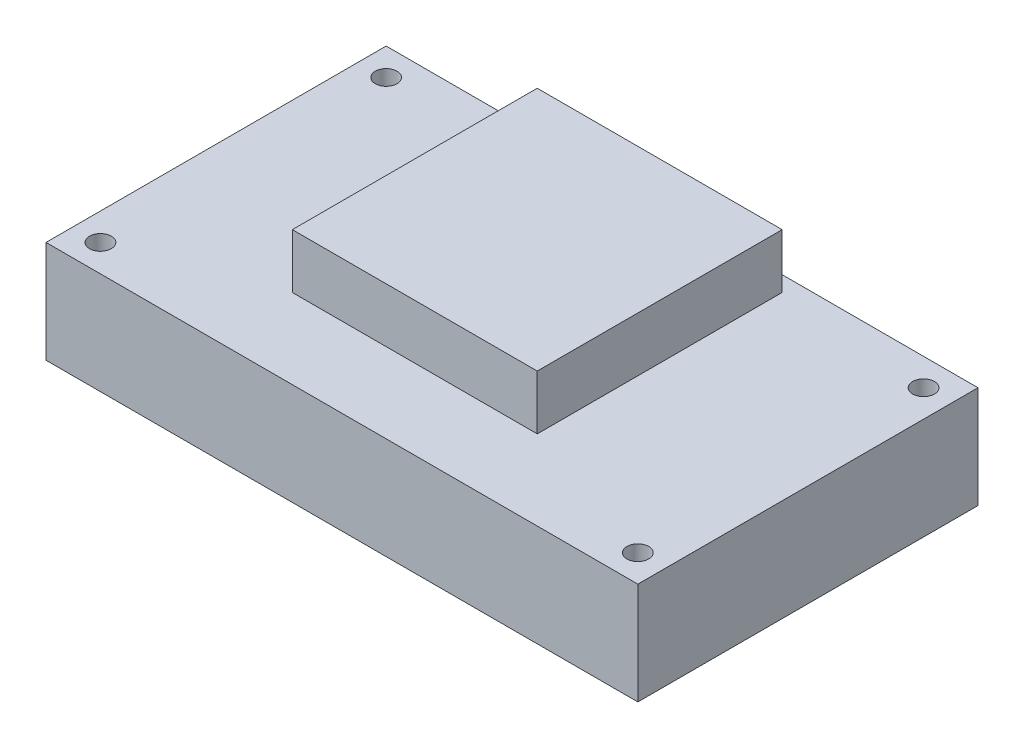
SolidWorks part; units mm, degrees
ref_plane "前视基准面" through (0, 0, 0) normal (0, 0, 1) x (1, 0, 0)
ref_plane "上视基准面" through (0, 0, 0) normal (0, 1, 0) x (1, 0, 0)
ref_plane "右视基准面" through (0, 0, 0) normal (1, 0, 0) x (0, 0, -1)
sketch "草图1" plane through (0, 0, 0) normal (0, 1, 0) x (1, 0, 0)
  line L0 (0, -55) -> (0, 55) construction
  line L1 (-43.5, 25) -> (43.5, 25)
  line L2 (-43.5, 25) -> (-43.5, -25)
  line L3 (-43.5, -25) -> (43.5, -25)
  line L4 (43.5, 25) -> (43.5, -25)
  line L5 (-43.5, 25) -> (43.5, -25) construction
  line L6 (-43.5, -25) -> (43.5, 25) construction
  line L7 (-55, 0) -> (55, 0) construction
  circle A0 centre (-39.5, 21) radius 1.6
  circle A1 centre (39.5, 21) radius 1.6
  circle A2 centre (39.5, -21) radius 1.6
  circle A3 centre (-39.5, -21) radius 1.6
  point P0 (0, 0)
  dimension "D3" = 3.2
  dimension "D4" = 4
  dimension "D5" = 4
  dimension "D1" = 87
  dimension "D2" = 50
extrude "凸台-拉伸1" add sketch "草图1" along normal blind 15
sketch "草图2" plane through (0, 15, 0) normal (0, 1, 0) x (1, 0, 0)
  line L1 (-19.0227, 22.7324) -> (16.9773, 22.7324)
  line L2 (-19.0227, 22.7324) -> (-19.0227, -13.2676)
  line L3 (-19.0227, -13.2676) -> (16.9773, -13.2676)
  line L4 (16.9773, 22.7324) -> (16.9773, -13.2676)
  line L5 (-19.0227, 22.7324) -> (16.9773, -13.2676) construction
  line L6 (-19.0227, -13.2676) -> (16.9773, 22.7324) construction
  point P0 (-1.0227, 4.7324)
  dimension "D1" = 36
  dimension "D2" = 36
extrude "凸台-拉伸2" add sketch "草图2" along normal blind 8
